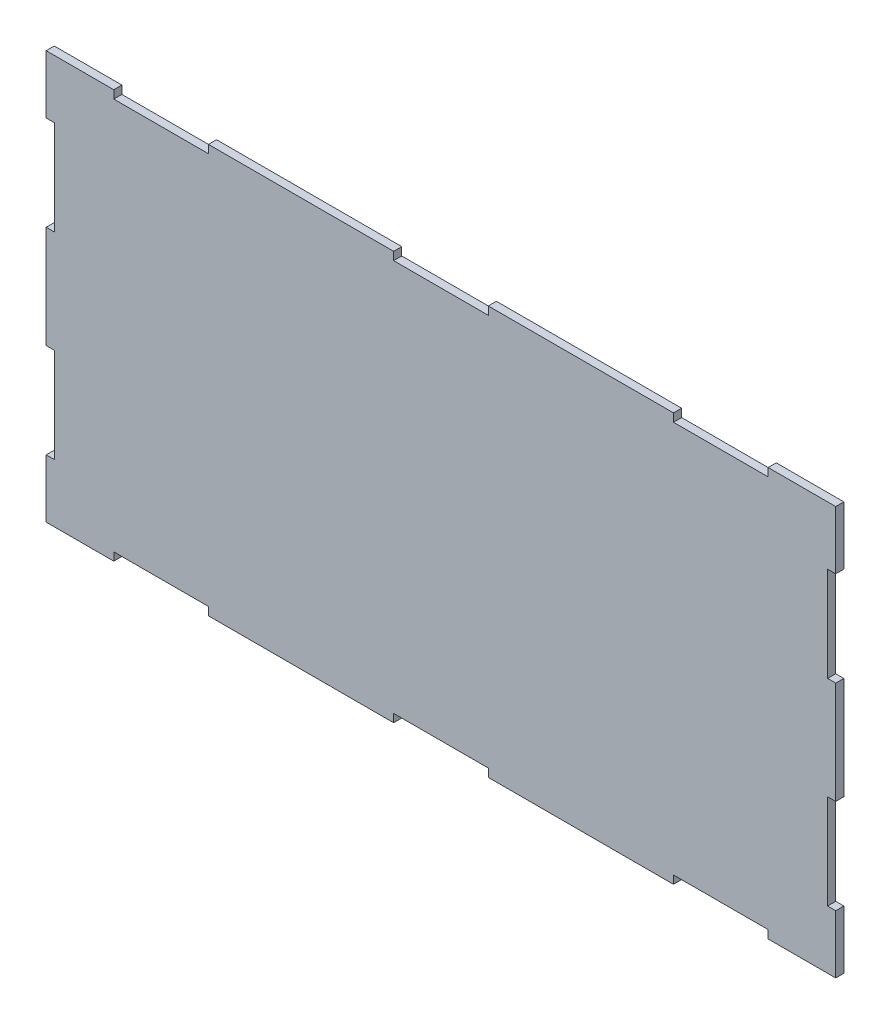
SolidWorks part; units mm, degrees
ref_plane "Front Plane" through (0, 0, 0) normal (0, 0, 1) x (1, 0, 0)
ref_plane "Top Plane" through (0, 0, 0) normal (0, 1, 0) x (1, 0, 0)
ref_plane "Right Plane" through (0, 0, 0) normal (1, 0, 0) x (0, 0, -1)
sketch "Sketch1" plane through (0, 0, 0) normal (0, 0, 1) x (1, 0, 0)
  line L1 (-146, 75.5) -> (146, 75.5)
  line L2 (-146, 75.5) -> (-146, -75.5)
  line L3 (-146, -75.5) -> (146, -75.5)
  line L4 (146, 75.5) -> (146, -75.5)
  line L5 (-146, 75.5) -> (146, -75.5) construction
  line L6 (-146, -75.5) -> (146, 75.5) construction
  point P0 (0, 0)
  dimension "D1" = 292
  dimension "D2" = 151
extrude "Boss-Extrude1" add sketch "Sketch1" along normal blind 3
sketch "Sketch2" plane through (0, 0, 3) normal (0, 0, 1) x (1, 0, 0)
  line L0 (146, 75.5) -> (-146, 75.5) construction
  line L1 (86, 72.5) -> (121, 72.5)
  line L2 (86, 72.5) -> (86, 75.5)
  line L3 (86, 75.5) -> (121, 75.5)
  line L4 (121, 72.5) -> (121, 75.5)
  line L5 (86, 72.5) -> (121, 75.5) construction
  line L6 (86, 75.5) -> (121, 72.5) construction
  line L7 (146, -75.5) -> (146, 75.5) construction
  line L9 (0, -1.65) -> (0, 1.65) construction
  line L10 (-86, 75.5) -> (-121, 75.5)
  line L11 (-121, 72.5) -> (-121, 75.5)
  line L12 (-86, 72.5) -> (-121, 72.5)
  line L13 (-86, 72.5) -> (-86, 75.5)
  line L14 (1.65, 0) -> (-1.65, 0) construction
  line L15 (-86, -72.5) -> (-86, -75.5)
  line L16 (-86, -72.5) -> (-121, -72.5)
  line L17 (-121, -72.5) -> (-121, -75.5)
  line L18 (-86, -75.5) -> (-121, -75.5)
  line L19 (86, -75.5) -> (121, -75.5)
  line L20 (121, -72.5) -> (121, -75.5)
  line L21 (86, -72.5) -> (121, -72.5)
  line L22 (86, -72.5) -> (86, -75.5)
  point P0 (103.5, 74)
  dimension "D1" = 3
  dimension "D2" = 35
  dimension "D3" = 0
  dimension "D4" = 25
extrude "Cut-Extrude1" cut sketch "Sketch2" against normal blind 3
sketch "Sketch4" plane through (0, 0, 0) normal (0, 0, 1) x (1, 0, 0)
  line L0 (0, -1.65) -> (0, 1.65) construction
  line L1 (-17.5, -72.5) -> (17.5, -72.5)
  line L2 (-17.5, -72.5) -> (-17.5, -75.5)
  line L3 (-17.5, -75.5) -> (17.5, -75.5)
  line L4 (17.5, -72.5) -> (17.5, -75.5)
  line L5 (-17.5, -72.5) -> (17.5, -75.5) construction
  line L6 (-17.5, -75.5) -> (17.5, -72.5) construction
  line L7 (-86, -75.5) -> (86, -75.5) construction
  line L8 (1.65, 0) -> (-1.65, 0) construction
  line L9 (-17.5, 75.5) -> (17.5, 75.5)
  line L10 (17.5, 72.5) -> (17.5, 75.5)
  line L11 (-17.5, 72.5) -> (17.5, 72.5)
  line L12 (-17.5, 72.5) -> (-17.5, 75.5)
  point P0 (0, -74)
  dimension "D1" = 0
  dimension "D2" = 0
  dimension "D3" = 3
  dimension "D4" = 35
extrude "Cut-Extrude2" cut sketch "Sketch4" along normal blind 3
sketch "Sketch5" plane through (146, 0, 0) normal (1, 0, 0) x (0, 0, -1)
  line L0 (-3, -75.5) -> (0, -75.5) construction
  line L1 (-3, -18.95) -> (0, -18.95)
  line L2 (-3, -18.95) -> (-3, -53.95)
  line L3 (-3, -53.95) -> (0, -53.95)
  line L4 (0, -18.95) -> (0, -53.95)
  line L5 (-3, -18.95) -> (0, -53.95) construction
  line L6 (-3, -53.95) -> (0, -18.95) construction
  line L7 (-3, -75.5) -> (-3, 75.5) construction
  line L8 (1.65, 0) -> (-1.65, 0) construction
  line L9 (-3, 53.95) -> (0, 53.95)
  line L10 (0, 18.95) -> (0, 53.95)
  line L11 (-3, 18.95) -> (0, 18.95)
  line L12 (-3, 18.95) -> (-3, 53.95)
  point P0 (-1.5, -36.45)
  dimension "D1" = 21.55
  dimension "D2" = 35
  dimension "D3" = 3
  dimension "D4" = 0
extrude "Cut-Extrude3" cut sketch "Sketch5" against normal blind 3
sketch "Sketch7" plane through (-146, 0, 0) normal (-1, 0, 0) x (0, 0, 1)
  line L0 (3, -75.5) -> (0, -75.5) construction
  line L1 (3, -18.95) -> (0, -18.95)
  line L2 (3, -18.95) -> (3, -53.95)
  line L3 (3, -53.95) -> (0, -53.95)
  line L4 (0, -18.95) -> (0, -53.95)
  line L5 (3, -18.95) -> (0, -53.95) construction
  line L6 (3, -53.95) -> (0, -18.95) construction
  line L7 (3, 75.5) -> (3, -75.5) construction
  line L8 (1.65, 0) -> (-1.65, 0) construction
  line L9 (3, 53.95) -> (0, 53.95)
  line L10 (3, 18.95) -> (3, 53.95)
  line L11 (0, 18.95) -> (0, 53.95)
  line L12 (3, 18.95) -> (0, 18.95)
  point P0 (1.5, -36.45)
  dimension "D1" = 3
  dimension "D2" = 35
  dimension "D3" = 21.55
  dimension "D4" = 0
extrude "Cut-Extrude4" cut sketch "Sketch7" against normal blind 3
equation "\"`37\"=36"
